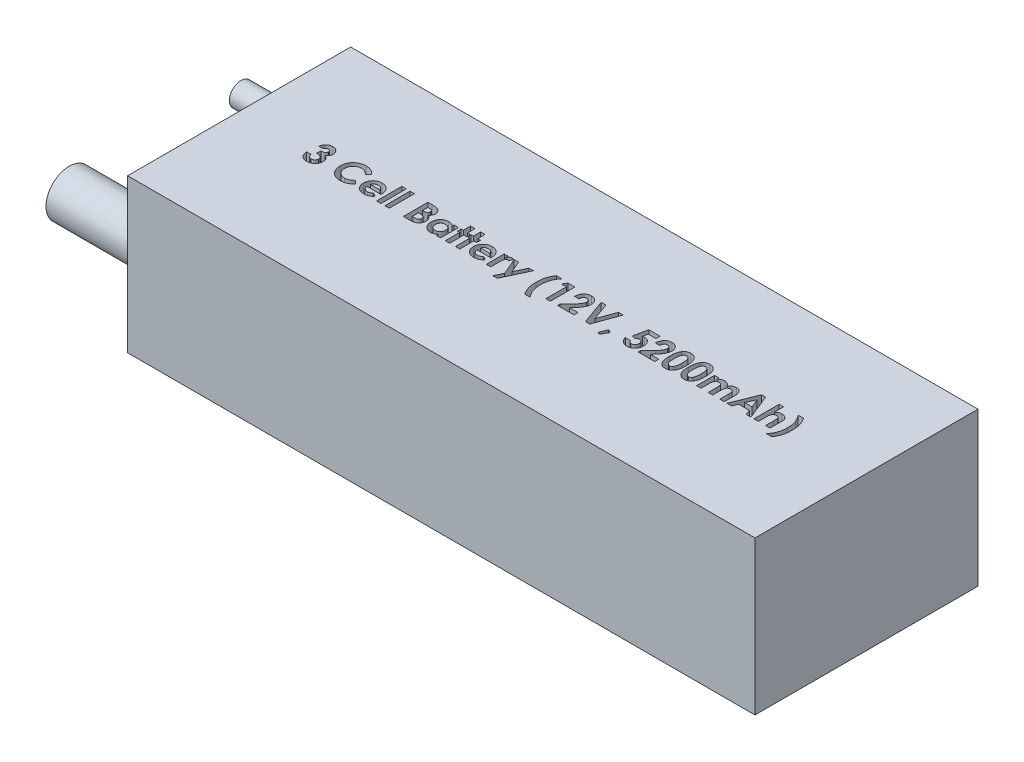
SolidWorks part; units mm, degrees
ref_plane "Front Plane" through (0, 0, 0) normal (0, 0, 1) x (1, 0, 0)
ref_plane "Top Plane" through (0, 0, 0) normal (0, 1, 0) x (1, 0, 0)
ref_plane "Right Plane" through (0, 0, 0) normal (1, 0, 0) x (0, 0, -1)
sketch "Sketch1" plane through (0, 0, 0) normal (0, 1, 0) x (1, 0, 0)
  line L1 (0, 0) -> (135, 0)
  line L2 (0, 0) -> (0, 48)
  line L3 (0, 48) -> (135, 48)
  line L4 (135, 0) -> (135, 48)
  dimension "D1" = 135
  dimension "D2" = 48
extrude "Boss-Extrude1" add sketch "Sketch1" along normal blind 33
sketch "Sketch2" plane through (0, 0, 0) normal (-1, 0, 0) x (0, 0, 1)
  circle A0 centre (-7.4304, 16.0696) radius 5
  circle A1 centre (-44.3892, 16.0696) radius 2.5
  dimension "D1" = 5
  dimension "D2" = 10
extrude "Boss-Extrude2" add sketch "Sketch2" along normal blind 20
sketch "Sketch3" plane through (0, 33, 0) normal (0, 1, 0) x (1, 0, 0)
  text T0 "3 Cell Battery (12V, 5200mAh)" font "Century Gothic" height in points 20
extrude "Cut-Extrude1" cut sketch "Sketch3" against normal blind 5
